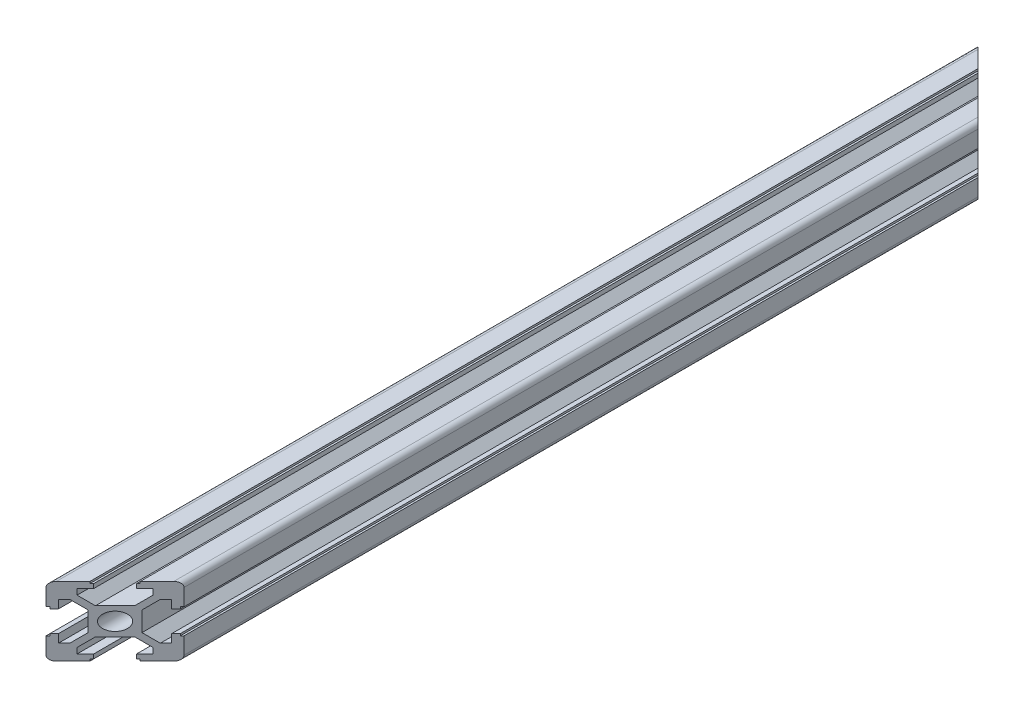
SolidWorks part; units mm, degrees
material "6063-T5"
ref_plane "前视基准面" through (0, 0, 0) normal (0, 0, 1) x (1, 0, 0)
ref_plane "上视基准面" through (0, 0, 0) normal (0, 1, 0) x (1, 0, 0)
ref_plane "右视基准面" through (0, 0, 0) normal (1, 0, 0) x (0, 0, -1)
sketch "草图2" plane through (0, 0, 0) normal (0, 0, 1) x (1, 0, 0)
  line L0 (-3.9, 2.8393) -> (-6.5607, 5.5)
  line L1 (-2.8393, 3.9) -> (2.8393, 3.9)
  line L2 (-3.9, 2.8393) -> (-3.9, -2.8393)
  line L3 (-2.8393, -3.9) -> (2.8393, -3.9)
  line L4 (3.9, 2.8393) -> (3.9, -2.8393)
  line L5 (-3.9, 3.9) -> (3.9, -3.9) construction
  line L6 (-3.9, -3.9) -> (3.9, 3.9) construction
  line L7 (-2.8393, 3.9) -> (-5.5, 6.5607)
  line L8 (-5.5, 6.5607) -> (-5.5, 8.2)
  line L9 (-5.5, 8.2) -> (-3.1, 8.2)
  line L10 (-3.1, 8.2) -> (-3.1, 9.45)
  line L11 (-3.1, 9.45) -> (-3.65, 9.45)
  line L12 (-3.65, 9.45) -> (-3.65, 10)
  line L13 (-3.65, 10) -> (-8.5, 10)
  line L14 (-6.5607, 5.5) -> (-8.2, 5.5)
  line L15 (-10, 3.65) -> (-10, 8.5)
  line L16 (-9.45, 3.65) -> (-10, 3.65)
  line L17 (-9.45, 3.1) -> (-9.45, 3.65)
  line L18 (-8.2, 3.1) -> (-9.45, 3.1)
  line L19 (-8.2, 5.5) -> (-8.2, 3.1)
  line L20 (2.8393, 3.9) -> (5.5, 6.5607)
  line L21 (3.9, 2.8393) -> (6.5607, 5.5)
  line L22 (6.5607, 5.5) -> (8.2, 5.5)
  line L23 (8.2, 5.5) -> (8.2, 3.1)
  line L24 (8.2, 3.1) -> (9.45, 3.1)
  line L25 (9.45, 3.1) -> (9.45, 3.65)
  line L26 (9.45, 3.65) -> (10, 3.65)
  line L27 (10, 3.65) -> (10, 8.5)
  line L28 (5.5, 6.5607) -> (5.5, 8.2)
  line L29 (3.65, 10) -> (8.5, 10)
  line L30 (3.65, 9.45) -> (3.65, 10)
  line L31 (3.1, 9.45) -> (3.65, 9.45)
  line L32 (3.1, 8.2) -> (3.1, 9.45)
  line L33 (5.5, 8.2) -> (3.1, 8.2)
  line L34 (3.9, -2.8393) -> (6.5607, -5.5)
  line L35 (2.8393, -3.9) -> (5.5, -6.5607)
  line L36 (5.5, -6.5607) -> (5.5, -8.2)
  line L37 (5.5, -8.2) -> (3.1, -8.2)
  line L38 (3.1, -8.2) -> (3.1, -9.45)
  line L39 (3.1, -9.45) -> (3.65, -9.45)
  line L40 (3.65, -9.45) -> (3.65, -10)
  line L41 (3.65, -10) -> (8.5, -10)
  line L42 (6.5607, -5.5) -> (8.2, -5.5)
  line L43 (10, -3.65) -> (10, -8.5)
  line L44 (9.45, -3.65) -> (10, -3.65)
  line L45 (9.45, -3.1) -> (9.45, -3.65)
  line L46 (8.2, -3.1) -> (9.45, -3.1)
  line L47 (8.2, -5.5) -> (8.2, -3.1)
  line L48 (-2.8393, -3.9) -> (-5.5, -6.5607)
  line L49 (-3.9, -2.8393) -> (-6.5607, -5.5)
  line L50 (-6.5607, -5.5) -> (-8.2, -5.5)
  line L51 (-8.2, -5.5) -> (-8.2, -3.1)
  line L52 (-8.2, -3.1) -> (-9.45, -3.1)
  line L53 (-9.45, -3.1) -> (-9.45, -3.65)
  line L54 (-9.45, -3.65) -> (-10, -3.65)
  line L55 (-10, -3.65) -> (-10, -8.5)
  line L56 (-5.5, -6.5607) -> (-5.5, -8.2)
  line L57 (-3.65, -10) -> (-8.5, -10)
  line L58 (-3.65, -9.45) -> (-3.65, -10)
  line L59 (-3.1, -9.45) -> (-3.65, -9.45)
  line L60 (-3.1, -8.2) -> (-3.1, -9.45)
  line L61 (-5.5, -8.2) -> (-3.1, -8.2)
  circle A0 centre (0, 0) radius 2.55
  arc A1 (-8.5, 10) -> (-10, 8.5) centre (-8.5, 8.5) ccw
  arc A2 (10, 8.5) -> (8.5, 10) centre (8.5, 8.5) ccw
  arc A3 (8.5, -10) -> (10, -8.5) centre (8.5, -8.5) ccw
  arc A4 (-10, -8.5) -> (-8.5, -10) centre (-8.5, -8.5) ccw
  point P25 (-10, 10)
  point P79 (0, 0)
  dimension "D1" = 5.1
  dimension "D9" = 1.5
  dimension "D2" = 7.8
  dimension "D3" = 1.5
  dimension "D4" = 10
  dimension "D5" = 3.1
  dimension "D6" = 0.55
  dimension "D7" = 1.8
  dimension "D8" = 5.5
  dimension "D11" = 3.9
  dimension "D10" = 4
extrude "凸台-拉伸1" add sketch "草图2" along normal blind 270
sketch "草图3" plane through (0, 10, 0) normal (0, 1, 0) x (1, 0, 0)
  line L0 (-10, 0) -> (10, -20)
  line L1 (10, -270) -> (10, 0) construction
  line L2 (10, -20) -> (10, 0)
  line L3 (10, 0) -> (-10, 0)
  line L4 (-10, -270) -> (-10, 0) construction
  line L5 (-10, -270) -> (10, -250)
  line L6 (10, -250) -> (10, -270)
  line L7 (10, -270) -> (-10, -270)
  dimension "D1" = 20
  dimension "D2" = 20
extrude "切除-拉伸1" cut sketch "草图3" against normal blind 38
